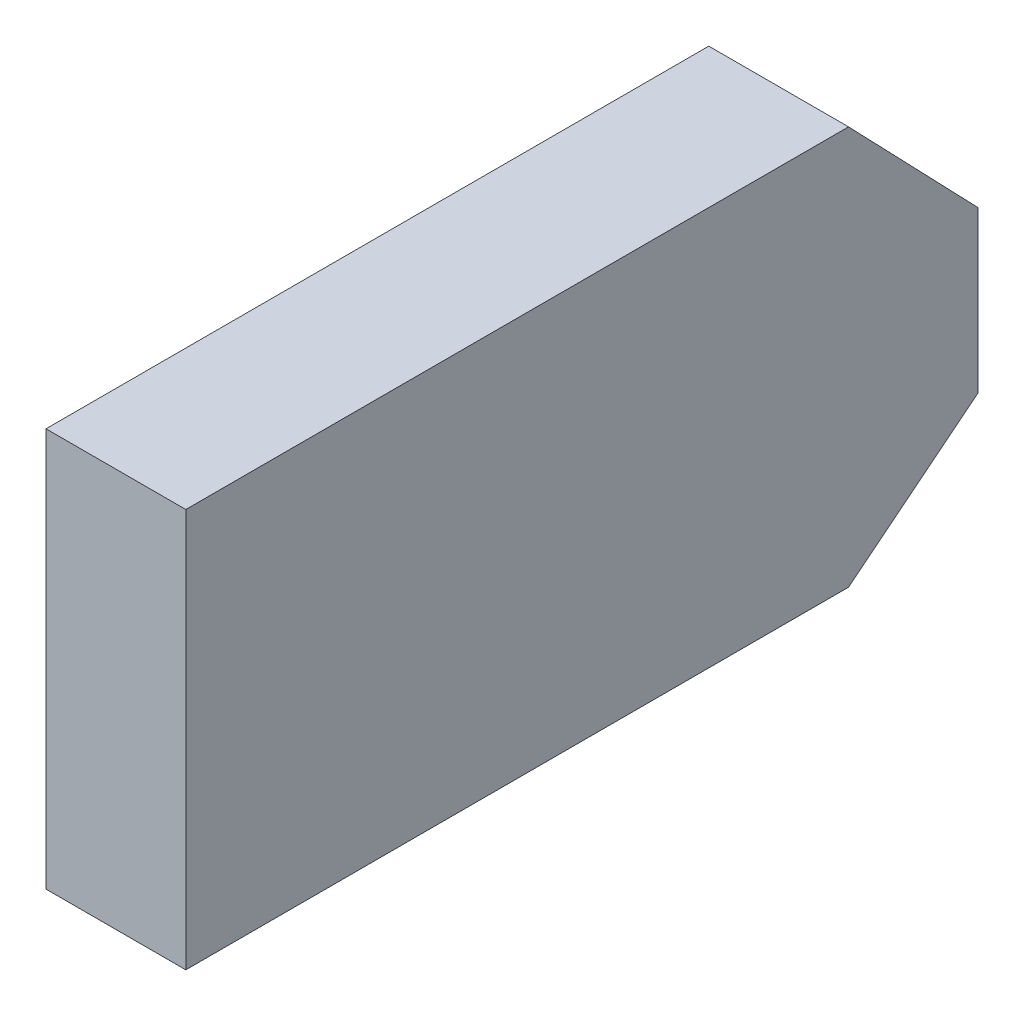
SolidWorks part; units mm, degrees
ref_plane "Front Plane" through (0, 0, 0) normal (0, 0, 1) x (1, 0, 0)
ref_plane "Top Plane" through (0, 0, 0) normal (0, 1, 0) x (1, 0, 0)
ref_plane "Right Plane" through (0, 0, 0) normal (1, 0, 0) x (0, 0, -1)
sketch "Sketch1" plane through (0, 0, 0) normal (1, 0, 0) x (0, 0, -1)
  line L0 (-18.7192, -107.2089) -> (124.6222, -107.2089) construction
sketch "Sketch4" plane through (0, 0, 0) normal (1, 0, 0) x (0, 0, -1)
  line L0 (55.5, 10.5) -> (132.5, 10.5)
  line L1 (132.5, 10.5) -> (137, 14)
  line L2 (137, 14) -> (137, 40)
  line L3 (137, 40) -> (127.5, 51)
  line L4 (127.5, 51) -> (83.5, 51)
  line L5 (83.5, 51) -> (55.5, 27)
  line L6 (55.5, 27) -> (55.5, 10.5)
  dimension "D1" = 77
  dimension "D2" = 4.5
  dimension "D3" = 3.5
  dimension "D4" = 72
  dimension "D5" = 26
  dimension "D6" = 55.5
  dimension "D7" = 10.5
  dimension "D8" = 40.5
  dimension "D9" = 28
  dimension "D10" = 16.5
sketch "Sketch2" plane through (0, 0, 0) normal (1, 0, 0) x (0, 0, -1)
  line L0 (0, 0) -> (0, 77)
  line L1 (0, 77) -> (128, 77)
  line L2 (128, 77) -> (153, 51)
  line L3 (153, 51) -> (153, 20)
  line L4 (153, 20) -> (128, 0)
  line L5 (128, 0) -> (0, 0)
  line L6 (0, 77) -> (0, 104) construction
  line L7 (128, 77) -> (145, 77) construction
  line L8 (145, 77) -> (145, 104) construction
  circle A0 centre (10.5, 90.5) radius 3.6414 construction
  circle A1 centre (23, 90.5) radius 3.5671 construction
  circle A2 centre (36, 90.5) radius 3.2818 construction
  point P16 (0, 90.5)
  dimension "D1" = 77
  dimension "D2" = 27
  dimension "D3" = 153
  dimension "D4" = 20
  dimension "D5" = 128
  dimension "D6" = 128
  dimension "D7" = 31
  dimension "D8" = 17
  dimension "D9" = 27
  dimension "D10" = 10.5
  dimension "D11" = 23
  dimension "D12" = 36
extrude "Boss-Extrude1" add sketch "Sketch2" along normal blind 27
sketch "Sketch3" plane through (0, 0, 0) normal (1, 0, 0) x (0, 0, -1)
  line L1 (6.529, -4.8244) -> (121.529, -4.8244)
  line L2 (6.529, -4.8244) -> (6.529, -19.8244)
  line L3 (6.529, -19.8244) -> (121.529, -19.8244)
  line L4 (121.529, -4.8244) -> (121.529, -19.8244)
  dimension "D1" = 115
  dimension "D2" = 15
